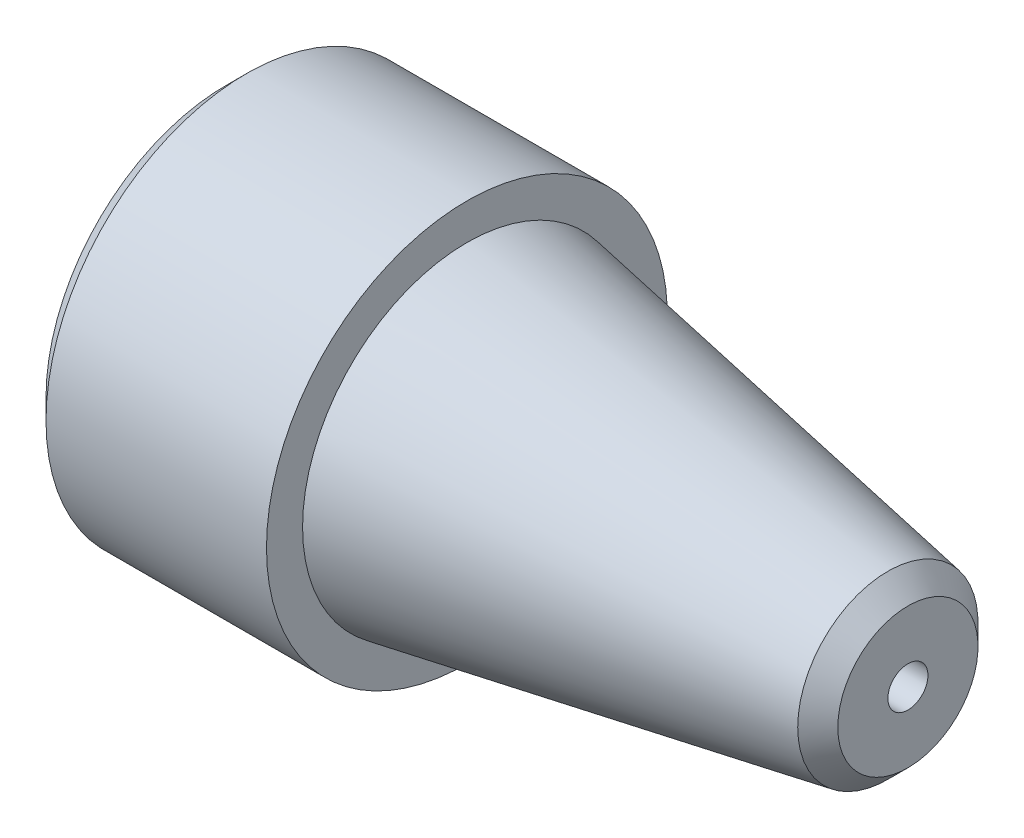
SolidWorks part; units mm, degrees
ref_plane "Plan de face" through (0, 0, 0) normal (0, 0, 1) x (1, 0, 0)
ref_plane "Plan de dessus" through (0, 0, 0) normal (0, 1, 0) x (1, 0, 0)
ref_plane "Plan de droite" through (0, 0, 0) normal (1, 0, 0) x (0, 0, -1)
sketch "Esquisse1" plane through (0, 0, 0) normal (0, 0, 1) x (1, 0, 0)
  line L0 (0, 9) -> (1, 10)
  line L1 (1, 10) -> (12, 10)
  line L2 (12, 10) -> (12, 8.2)
  line L3 (12, 8.2) -> (33, 4.4971)
  line L4 (33, 4.4971) -> (34, 3.4971)
  line L5 (34, 3.4971) -> (34, 1)
  line L6 (34, 1) -> (0, 1)
  line L7 (0, 1) -> (0, 9)
  line L8 (-9.5767, 0) -> (24.2583, 0) construction
  dimension "D1" = 8
  dimension "D2" = 1
  dimension "D3" = 135
  dimension "D4" = 11
  dimension "D5" = 170
  dimension "D6" = 21
  dimension "D7" = 1
  dimension "D8" = 2
  dimension "D9" = 7.2
revolve "Révolution1" add sketch "Esquisse1" angle 360 about L8
